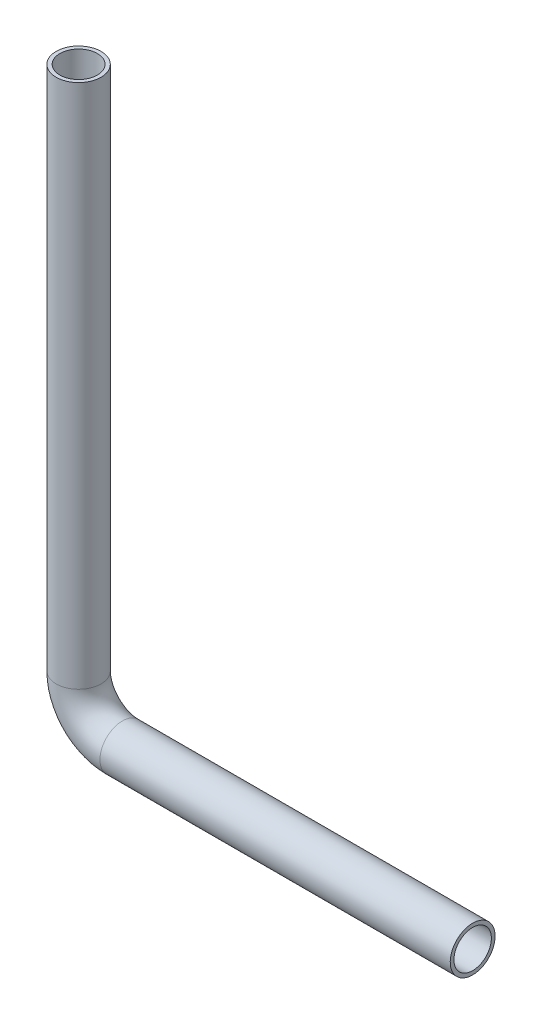
SolidWorks part; units mm, degrees
material "Alumina"
ref_plane "Plano frontal" through (0, 0, 0) normal (0, 0, 1) x (1, 0, 0)
ref_plane "Plano superior" through (0, 0, 0) normal (0, 1, 0) x (1, 0, 0)
ref_plane "Plano direito" through (0, 0, 0) normal (1, 0, 0) x (0, 0, -1)
sketch "Esboço5" plane through (0, 0, 0) normal (0, 0, 1) x (1, 0, 0)
  line L0 (0, 0) -> (-160, 0)
  line L1 (-180, 20) -> (-180, 260)
  arc A0 (-160, 0) -> (-180, 20) centre (-160, 20) cw
  point P6 (-180, 0)
  dimension "D3" = 20
  dimension "D1" = 260
  dimension "D2" = 180
ref_plane "Plano1" through (0, 0, 0) normal (-1, 0, 0) x (0, 0, 1)
sketch "Esboço6" plane through (0, 0, 0) normal (-1, 0, 0) x (0, 0, 1)
  circle A0 centre (0, 0) radius 10.25
  circle A2 centre (0, 0) radius 8.55
  dimension "D1" = 20.5
  dimension "D2" = 1.7
sweep "Varredura1" add profiles "Esboço6" path "Esboço5"
ref_plane "Plano2" through (-195, 0, 0) normal (-1, 0, 0) x (0, 0, 1)
hole_wizard "Furo roscado de M61" positions "Esboço7" profile "Esboço9" tap size "M6" standard "DIN"
sketch "Esboço7" plane through (-195, 0, 0) normal (-1, 0, 0) x (0, 0, 1)
  line L0 (10.25, 260) -> (-10.25, 260) construction
  line L1 (-10.25, 260) -> (-10.25, 20) construction
  point P0 (0, 240)
  point P6 (0, 215)
  point P8 (0, 190)
  point P10 (0, 165)
  dimension "D1" = 20
  dimension "D2" = 25
  dimension "D3" = 25
  dimension "D4" = 25
  dimension "D5" = 10.25
sketch "Esboço9" plane through (-195, 240, 0) normal (0, 1, 0) x (0, 0, 1)
  line L0 (0, 0) -> (0, 16.5022)
  line L1 (0, 16.5022) -> (2.5, 15)
  line L2 (2.5, 15) -> (2.5, 0)
  line L5 (2.5, 0) -> (0, 0)
  line L10 (0, 16.5022) -> (-2.5, 15) construction
  line L11 (0, -6.35) -> (0, 107.95) construction
  dimension "Tap Drill Dia." = 5
  dimension "Tap Drill Depth" = 15
  dimension "Drill Angle" = 118
cosmetic thread "Rosca de furo1" parameters "D1"=6.8237, "D2"=6
cosmetic thread "Rosca de furo2" parameters "D1"=6.8237, "D2"=6
cosmetic thread "Rosca de furo3" parameters "D1"=6.8237, "D2"=6
cosmetic thread "Rosca de furo4" parameters "D1"=6.8237, "D2"=6
